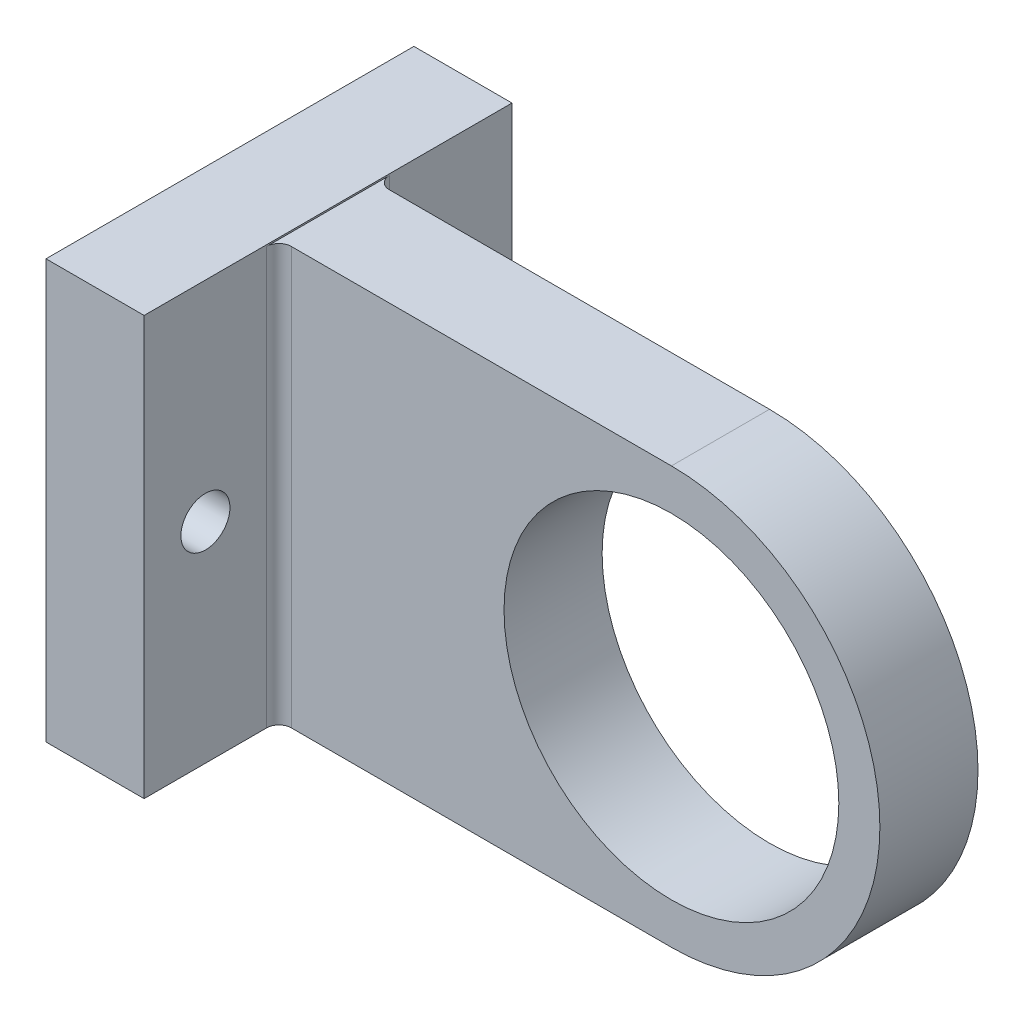
SolidWorks part; units mm, degrees
ref_plane "Front Plane" through (0, 0, 0) normal (0, 0, 1) x (1, 0, 0)
ref_plane "Top Plane" through (0, 0, 0) normal (0, 1, 0) x (1, 0, 0)
ref_plane "Right Plane" through (0, 0, 0) normal (1, 0, 0) x (0, 0, -1)
sketch "Sketch2" plane through (0, 0, 0) normal (0, 0, 1) x (1, 0, 0)
  line L4 (22.9129, 16.376) -> (22.9129, -18.1515) construction
  line L5 (22.9129, 16.1123) -> (-17.0871, 16.1123)
  line L6 (22.9129, -17.8877) -> (-17.0871, -17.8877)
  line L7 (-17.0871, 16.1123) -> (-17.0871, -17.8877)
  circle A0 centre (22.9129, -0.8877) radius 13.65
  arc A2 (22.9129, -17.8877) -> (22.9129, 16.1123) centre (22.9129, -0.8877) ccw
  dimension "D3" = 27.3
  dimension "D4" = 40
  dimension "D1" = 34
  dimension "D2" = 40
extrude "Boss-Extrude1" add sketch "Sketch2" along normal blind 8
sketch "Sketch3" plane through (-17.0871, 0, 0) normal (-1, 0, 0) x (0, 0, 1)
  line L0 (8, -17.8877) -> (0, -17.8877) construction
  line L1 (-11, 16.2392) -> (19, 16.2392)
  line L2 (-11, 16.2392) -> (-11, -17.8877)
  line L3 (-11, -17.8877) -> (19, -17.8877)
  line L4 (19, 16.2392) -> (19, -17.8877)
  point P4 (4, -17.8877)
  point P7 (4, -17.8877)
  dimension "D1" = 30
extrude "Boss-Extrude2" add sketch "Sketch3" against normal blind 8
fillet "Fillet1" radius 1 2 edges at (-9.0871, -0.8877, 0) (-9.0871, -0.8877, 8)
sketch "Sketch5" plane through (-17.0871, 0, 0) normal (-1, 0, 0) x (0, 0, 1)
  line L0 (4, 16.2392) -> (4, -17.8877) construction
  line L1 (19, 16.2392) -> (-11, 16.2392) construction
  line L2 (19, -17.8877) -> (-11, -17.8877) construction
  line L3 (-11, -0.8243) -> (19, -0.8243) construction
  line L4 (-11, 16.2392) -> (-11, -17.8877) construction
  line L5 (19, -17.8877) -> (19, 16.2392) construction
  circle A0 centre (-6, -0.8243) radius 2
  circle A1 centre (14, -0.8243) radius 2
  dimension "D1" = 4
  dimension "D2" = 4
  dimension "D3" = 5
  dimension "D4" = 5
extrude "Cut-Extrude2" cut sketch "Sketch5" against normal through all contours A1 | A0
